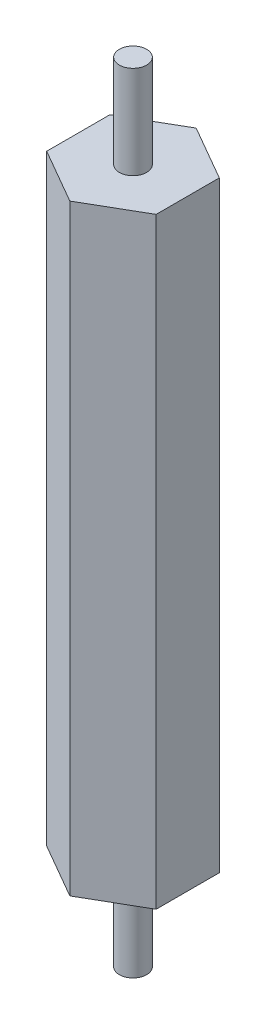
SolidWorks part; units mm, degrees
ref_plane "正面" through (0, 0, 0) normal (0, 0, 1) x (1, 0, 0)
ref_plane "平面" through (0, 0, 0) normal (0, 1, 0) x (1, 0, 0)
ref_plane "右側面" through (0, 0, 0) normal (1, 0, 0) x (0, 0, -1)
sketch "ｽｹｯﾁ1" plane through (0, 0, 0) normal (0, 1, 0) x (1, 0, 0)
  line L1 (10.0018, -5.7703) -> (9.9981, 5.7767)
  line L2 (9.9981, 5.7767) -> (-0.0037, 11.547)
  line L3 (-0.0037, 11.547) -> (-10.0018, 5.7703)
  line L4 (-10.0018, 5.7703) -> (-9.9981, -5.7767)
  line L5 (-9.9981, -5.7767) -> (0.0037, -11.547)
  line L6 (0.0037, -11.547) -> (10.0018, -5.7703)
  circle A0 centre (0, 0) radius 10 construction
  dimension "D1" = 20
extrude "ﾎﾞｽ - 押し出し1" add sketch "ｽｹｯﾁ1" along normal blind 110
sketch "ｽｹｯﾁ3" plane through (0, 110, 0) normal (0, 1, 0) x (1, 0, 0)
  circle A0 centre (0, 0) radius 2.5
  dimension "D1" = 5
extrude "ﾎﾞｽ - 押し出し2" add sketch "ｽｹｯﾁ3" along normal blind 17
sketch "ｽｹｯﾁ4" plane through (0, 0, 0) normal (0, -1, 0) x (1, 0, 0)
  circle A0 centre (0, 0) radius 2.5
  dimension "D1" = 5
extrude "ﾎﾞｽ - 押し出し3" add sketch "ｽｹｯﾁ4" along normal blind 17
